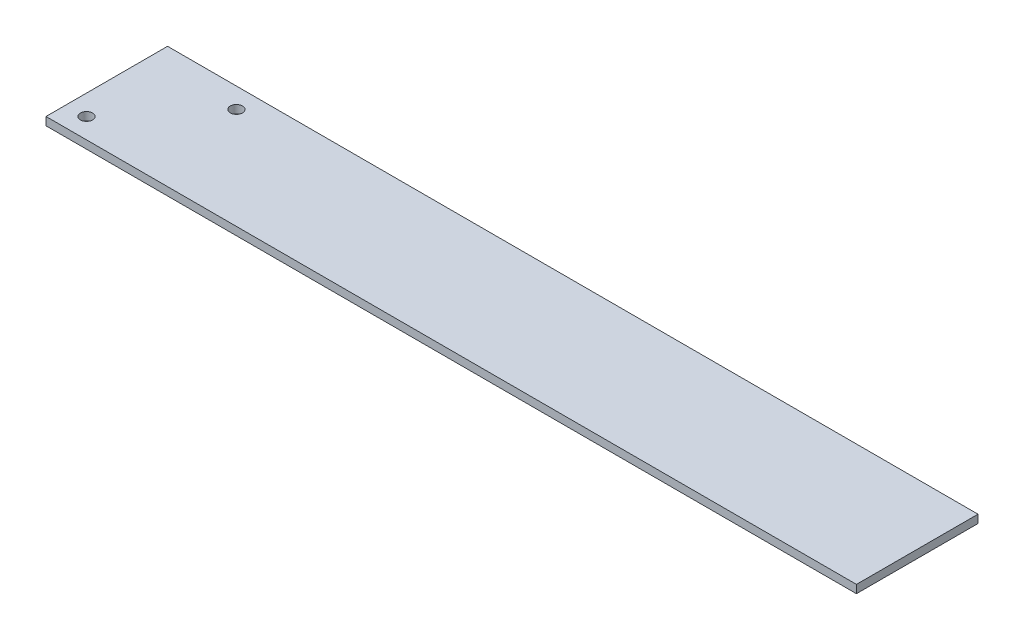
SolidWorks part; units mm, degrees
ref_plane "Front Plane" through (0, 0, 0) normal (0, 0, 1) x (1, 0, 0)
ref_plane "Top Plane" through (0, 0, 0) normal (0, 1, 0) x (1, 0, 0)
ref_plane "Right Plane" through (0, 0, 0) normal (1, 0, 0) x (0, 0, -1)
sketch "Sketch1" plane through (0, 0, 0) normal (0, 1, 0) x (1, 0, 0)
  line L1 (-100, 15) -> (100, 15)
  line L2 (-100, 15) -> (-100, -15)
  line L3 (-100, -15) -> (100, -15)
  line L4 (100, 15) -> (100, -15)
  line L5 (-100, 15) -> (100, -15) construction
  line L6 (-100, -15) -> (100, 15) construction
  circle A0 centre (-95, -10) radius 1.5
  circle A1 centre (-78, 10) radius 1.5
  point P0 (0, 0)
  dimension "D3" = 3
  dimension "D4" = 3
  dimension "D5" = 5
  dimension "D6" = 5
  dimension "D7" = 22
  dimension "D8" = 5
  dimension "D1" = 200
  dimension "D2" = 30
extrude "Boss-Extrude1" add sketch "Sketch1" along normal blind 2
